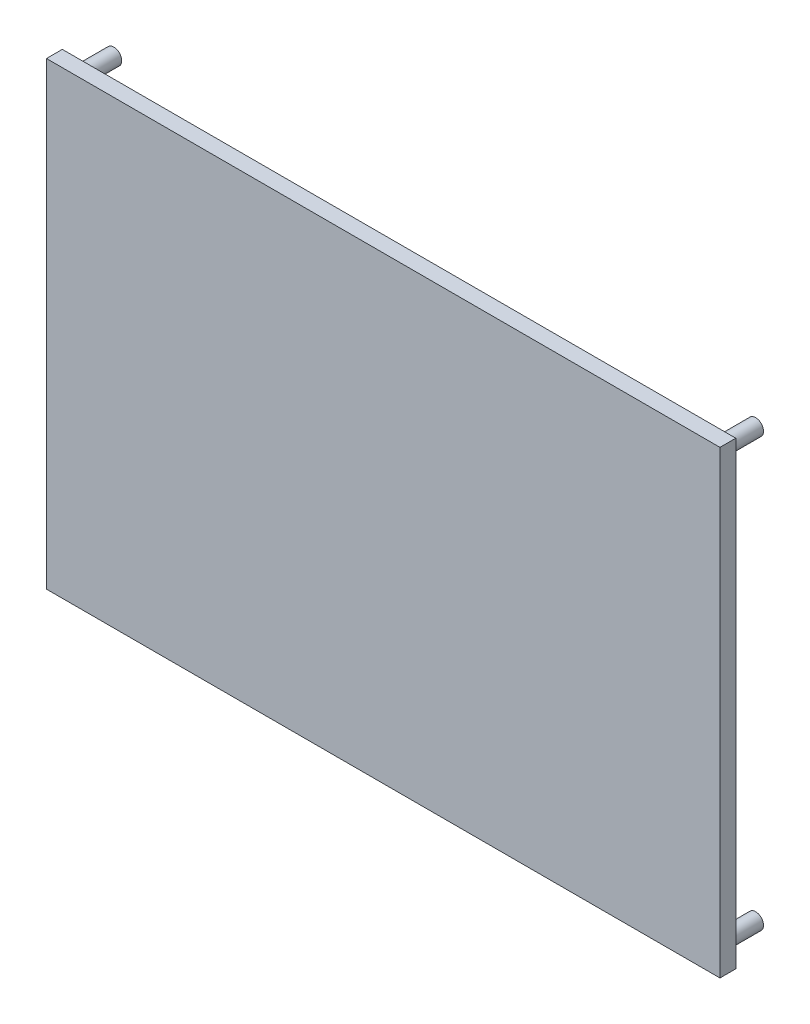
SolidWorks part; units mm, degrees
ref_plane "Front Plane" through (0, 0, 0) normal (0, 0, 1) x (1, 0, 0)
ref_plane "Top Plane" through (0, 0, 0) normal (0, 1, 0) x (1, 0, 0)
ref_plane "Right Plane" through (0, 0, 0) normal (1, 0, 0) x (0, 0, -1)
sketch "Sketch1" plane through (0, 0, 0) normal (0, 0, 1) x (1, 0, 0)
  line L1 (0, 0) -> (-85, 0)
  line L2 (0, 0) -> (0, 58)
  line L3 (0, 58) -> (-85, 58)
  line L4 (-85, 0) -> (-85, 58)
  dimension "D1" = 85
  dimension "D2" = 58
extrude "Boss-Extrude1" add sketch "Sketch1" along normal blind 2
sketch "Sketch2" plane through (0, 0, 2) normal (0, 0, 1) x (1, 0, 0)
  line L0 (-85, 0) -> (0, 0) construction
  line L1 (0, 58) -> (-85, 58) construction
  circle A0 centre (-83, 56) radius 1
  circle A1 centre (-2, 56) radius 1
  circle A2 centre (-83, 2) radius 1
  circle A3 centre (-2, 2) radius 1
  dimension "D1" = 2
  dimension "D5" = 2
  dimension "D2" = 2
  dimension "D3" = 2
  dimension "D6" = 2
  dimension "D7" = 2
  dimension "D4" = 2
  dimension "D8" = 2
extrude "Boss-Extrude3" add sketch "Sketch2" against normal blind 6.5
sketch "Sketch3" plane through (0, 0, 2) normal (0, 0, 1) x (1, 0, 0)
  line L0 (-85, 58) -> (-85, 0)
  line L1 (-85, 0) -> (0, 0)
sketch "Sketch4" plane through (0, 0, 2) normal (0, 0, 1) x (1, 0, 0)
  line L0 (-85, 58) -> (-85, 0)
  line L1 (-85, 0) -> (0, 0)
  line L2 (0, 0) -> (0, 58)
  line L3 (0, 58) -> (-85, 58)
  dimension "D1" = 85
  dimension "D2" = 58
